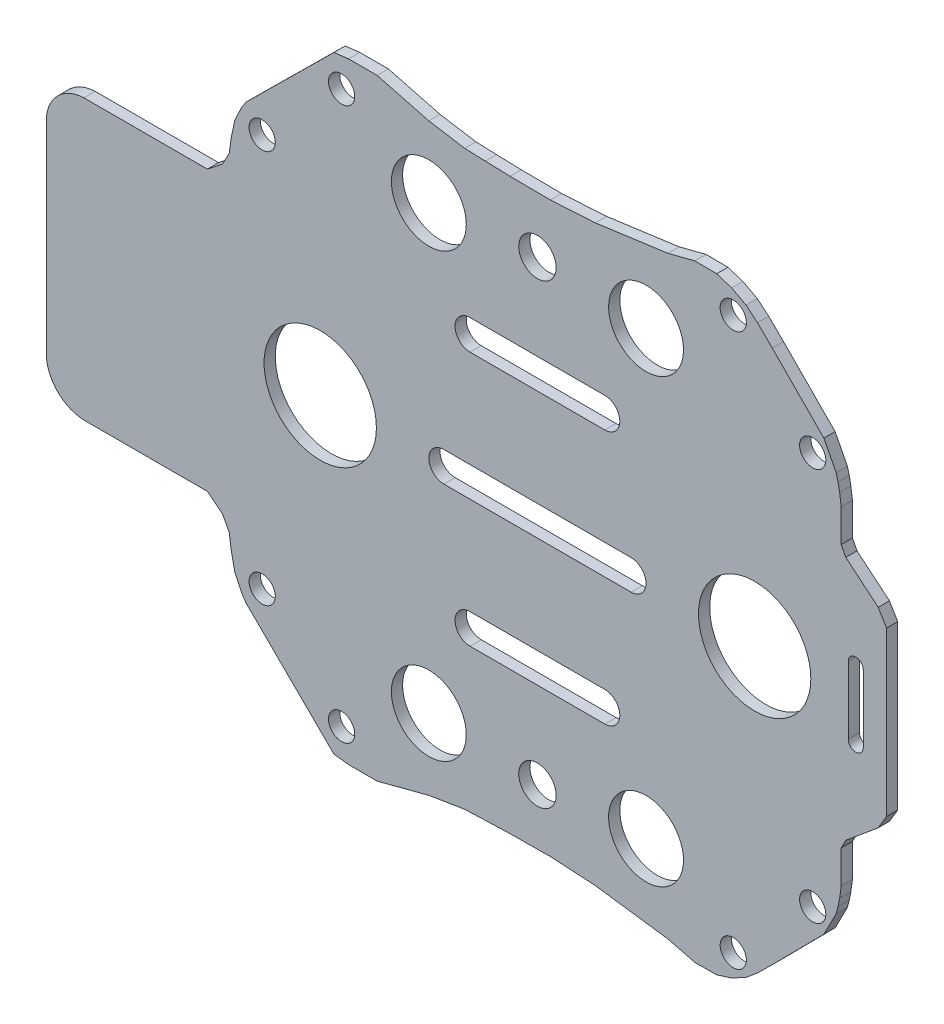
SolidWorks part; units mm, degrees
ref_plane "前视基准面" through (0, 0, 0) normal (0, 0, 1) x (1, 0, 0)
ref_plane "上视基准面" through (0, 0, 0) normal (0, 1, 0) x (1, 0, 0)
ref_plane "右视基准面" through (0, 0, 0) normal (1, 0, 0) x (0, 0, -1)
sketch "down_board" plane through (0, 0, 0) normal (0, 0, 1) x (1, 0, 0)
  line L0 (1242.6172, -299.3092) -> (1242.6172, -1264.6425) construction
  line L1 (-29, 0) -> (29, 0) construction
  line L2 (0, 0) -> (0, 12.9219) construction
  line L3 (-26.1434, 36.8566) -> (-36.75, 26.25) construction
  line L4 (0, 0) -> (62.6729, 0) construction
  line L5 (-65.5778, 13.4268) -> (-65.5778, -13.4268)
  line L6 (-9, -17) -> (9, -17) construction
  line L7 (-9, -15) -> (9, -15)
  line L8 (-60.5521, 18.6313) -> (-44.0689, 18.6313)
  line L9 (-44.0689, 18.6313) -> (-44.0689, 21.9081) construction
  line L10 (-44.0689, 21.9081) -> (-41.1491, 21.9081) construction
  line L11 (-44.0689, 18.6313) -> (-42.048, 20.2299)
  line L12 (-42.048, 20.2299) -> (-41.1491, 21.9081)
  line L13 (-41.1491, 21.9081) -> (-40.8925, 23.7893)
  line L14 (-40.8925, 23.7893) -> (-40.4108, 26.1027)
  line L15 (-40.4108, 26.1027) -> (-39.4914, 28.0715)
  line L16 (-39.4914, 28.0715) -> (-38.8975, 28.9664)
  line L17 (-38.8975, 28.9664) -> (-27.1756, 40.5607)
  line L18 (-27.1756, 40.5607) -> (-25.2198, 40.8008)
  line L19 (-25.2198, 40.8008) -> (-21.3998, 40.8008)
  line L20 (-21.3998, 40.8008) -> (-14.5, 38.9938)
  line L21 (-14.5, 38.9938) -> (-9.7165, 38.2151)
  line L22 (-9.7165, 38.2151) -> (-6.9496, 38.112)
  line L23 (-6.9496, 38.112) -> (-3.6476, 38.0098)
  line L24 (-3.6476, 38.0098) -> (1.7398, 37.9588)
  line L25 (1.7398, 37.9588) -> (7.7345, 38.3167)
  line L26 (7.7345, 38.3167) -> (17.4005, 39.6362)
  line L27 (17.4005, 39.6362) -> (21.0173, 40.5607)
  line L28 (21.0173, 40.5607) -> (23.9302, 40.5331)
  line L29 (23.9302, 40.5331) -> (25.9305, 39.8973)
  line L30 (25.9305, 39.8973) -> (27.8477, 38.8704)
  line L31 (27.8477, 38.8704) -> (29.3733, 37.5982)
  line L32 (29.3733, 37.5982) -> (31.3561, 35.6477)
  line L33 (31.3561, 35.6477) -> (38.247, 28.6809)
  line L34 (38.247, 28.6809) -> (39.8905, 25.4926)
  line L35 (39.8905, 25.4926) -> (40.1332, 24.5431)
  line L36 (40.1332, 24.5431) -> (40.3478, 23.4578)
  line L37 (40.3478, 23.4578) -> (40.5594, 21.9081)
  line L38 (40.5594, 21.9081) -> (40.5594, 17.5394)
  line L39 (40.5594, 17.5394) -> (41.1683, 16.3581)
  line L40 (41.1683, 16.3581) -> (42.7906, 15.0053)
  line L41 (42.7906, 15.0053) -> (45.4995, 12.7464)
  line L42 (45.4995, 12.7464) -> (46.6054, 10.8932)
  line L43 (46.6054, 10.8932) -> (46.6054, -10.8932)
  line L44 (45.4995, -12.7464) -> (46.6054, -10.8932)
  line L45 (42.7906, -15.0053) -> (45.4995, -12.7464)
  line L46 (41.1683, -16.3581) -> (42.7906, -15.0053)
  line L47 (40.5594, -17.5394) -> (41.1683, -16.3581)
  line L48 (40.5594, -21.9081) -> (40.5594, -17.5394)
  line L49 (40.3478, -23.4578) -> (40.5594, -21.9081)
  line L50 (40.1332, -24.5431) -> (40.3478, -23.4578)
  line L51 (39.8905, -25.4926) -> (40.1332, -24.5431)
  line L52 (38.247, -28.6809) -> (39.8905, -25.4926)
  line L53 (31.3561, -35.6477) -> (38.247, -28.6809)
  line L54 (29.3733, -37.5982) -> (31.3561, -35.6477)
  line L55 (27.8477, -38.8704) -> (29.3733, -37.5982)
  line L56 (25.9305, -39.8973) -> (27.8477, -38.8704)
  line L57 (23.9302, -40.5331) -> (25.9305, -39.8973)
  line L58 (21.0173, -40.5607) -> (23.9302, -40.5331)
  line L59 (17.4005, -39.6362) -> (21.0173, -40.5607)
  line L60 (7.7345, -38.3167) -> (17.4005, -39.6362)
  line L61 (1.7398, -37.9588) -> (7.7345, -38.3167)
  line L62 (-3.6476, -38.0098) -> (1.7398, -37.9588)
  line L63 (-6.9496, -38.112) -> (-3.6476, -38.0098)
  line L64 (-9.7165, -38.2151) -> (-6.9496, -38.112)
  line L65 (-14.5, -38.9938) -> (-9.7165, -38.2151)
  line L66 (-21.3998, -40.8008) -> (-14.5, -38.9938)
  line L67 (-25.2198, -40.8008) -> (-21.3998, -40.8008)
  line L68 (-27.1756, -40.5607) -> (-25.2198, -40.8008)
  line L69 (-38.8975, -28.9664) -> (-27.1756, -40.5607)
  line L70 (-39.4914, -28.0715) -> (-38.8975, -28.9664)
  line L71 (-40.4108, -26.1027) -> (-39.4914, -28.0715)
  line L72 (-40.8925, -23.7893) -> (-40.4108, -26.1027)
  line L73 (-41.1491, -21.9081) -> (-40.8925, -23.7893)
  line L74 (-42.048, -20.2299) -> (-41.1491, -21.9081)
  line L75 (-44.0689, -18.6313) -> (-42.048, -20.2299)
  line L76 (-60.5521, -18.6313) -> (-44.0689, -18.6313)
  line L77 (-9, -19) -> (9, -19)
  line L78 (-12.5, 0) -> (12.5, 0) construction
  line L79 (-12.5, 2) -> (12.5, 2)
  line L80 (-12.5, -2) -> (12.5, -2)
  line L81 (-9, 17) -> (9, 17) construction
  line L82 (-9, 15) -> (9, 15)
  line L83 (-9, 19) -> (9, 19)
  line L84 (42.5, -4.5) -> (42.5, 4.5) construction
  line L85 (41.5, -4.5) -> (41.5, 4.5)
  line L86 (43.5, -4.5) -> (43.5, 4.5)
  circle A0 centre (-29, 0) radius 7.5
  circle A1 centre (29, 0) radius 7.5
  circle A2 centre (-14.5, 29.5) radius 5
  circle A3 centre (14.5, 29.5) radius 5
  circle A4 centre (14.5, -29.5) radius 5
  circle A5 centre (-14.5, -29.5) radius 5
  circle A6 centre (-36.75, 26.25) radius 1.75
  circle A7 centre (-26.1434, 36.8566) radius 1.75
  circle A8 centre (36.75, 26.25) radius 1.75
  circle A9 centre (26.1434, 36.8566) radius 1.75
  circle A10 centre (36.75, -26.25) radius 1.75
  circle A11 centre (26.1434, -36.8566) radius 1.75
  circle A12 centre (-36.75, -26.25) radius 1.75
  circle A13 centre (-26.1434, -36.8566) radius 1.75
  arc A14 (-65.5778, 13.4268) -> (-60.5521, 18.6313) centre (-60.3702, 13.4268) cw
  arc A15 (-65.5778, -13.4268) -> (-60.5521, -18.6313) centre (-60.3702, -13.4268) ccw
  circle A16 centre (0, -30.5) radius 2.5
  arc A17 (-9, -15) -> (-9, -19) centre (-9, -17) ccw
  arc A18 (9, -19) -> (9, -15) centre (9, -17) ccw
  arc A19 (-12.5, 2) -> (-12.5, -2) centre (-12.5, 0) ccw
  arc A20 (12.5, -2) -> (12.5, 2) centre (12.5, 0) ccw
  arc A21 (-9, 15) -> (-9, 19) centre (-9, 17) cw
  arc A22 (9, 19) -> (9, 15) centre (9, 17) cw
  arc A23 (41.5, -4.5) -> (43.5, -4.5) centre (42.5, -4.5) ccw
  arc A24 (43.5, 4.5) -> (41.5, 4.5) centre (42.5, 4.5) ccw
  circle A25 centre (0, 30.5) radius 2.5
  point P35 (-65.5778, 0)
  point P73 (-40.6516, 24.946)
  point P76 (28.6105, 38.2343)
  point P78 (46.6054, 0)
  point P89 (28.6105, -38.2343)
  point P107 (-40.6516, -24.946)
  point P116 (-65.5778, 0)
  point P119 (0, -17)
  point P126 (0, 0)
  point P133 (0, 17)
  point P140 (42.5, 0)
  dimension "D1" = 15
  dimension "D2" = 10
  dimension "D5" = 15
  dimension "D10" = 3.5
  dimension "D11" = 17
  dimension "D14" = 2
  dimension "D16" = 1
  dimension "D17" = 5
  dimension "D3" = 29.5
  dimension "D4" = 14.5
  dimension "D6" = 45
  dimension "D7" = 26.25
  dimension "D8" = 36.75
  dimension "D9" = 58
  dimension "D12" = 42.5
  dimension "D13" = 18
  dimension "D15" = 9
  dimension "D18" = 30.5
extrude "凸台-拉伸1" add sketch "down_board" along normal blind 1.5
